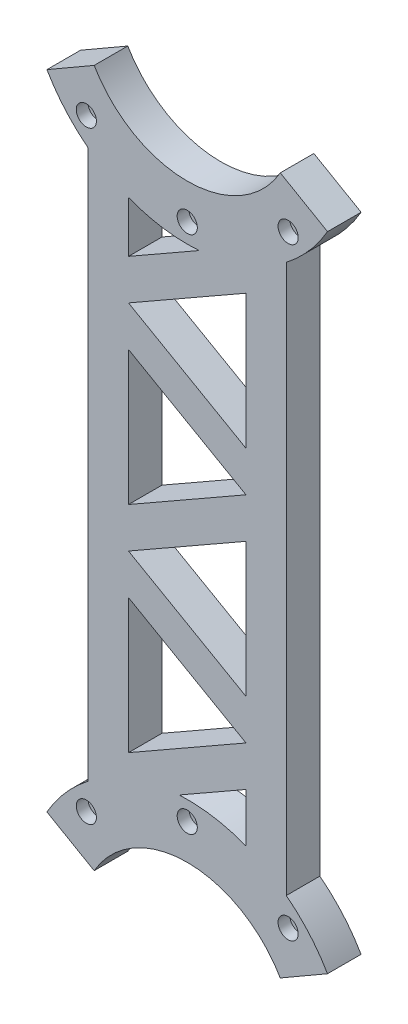
SolidWorks part; units mm, degrees
ref_plane "Front Plane" through (0, 0, 0) normal (0, 0, 1) x (1, 0, 0)
ref_plane "Top Plane" through (0, 0, 0) normal (0, 1, 0) x (1, 0, 0)
ref_plane "Right Plane" through (0, 0, 0) normal (1, 0, 0) x (0, 0, -1)
sketch "Sketch1" plane through (0, 0, 0) normal (0, 0, 1) x (1, 0, 0)
  circle A0 centre (0, 0) radius 48.25
extrude "Boss-Extrude1" add sketch "Sketch1" against normal blind 10 contours A0
sketch "Sketch2" plane through (0, 0, 0) normal (0, 0, 1) x (1, 0, 0)
  line L1 (-63.412, 28.4111) -> (-46.25, 28.4111)
  line L2 (-63.412, 28.4111) -> (-63.412, -28.4111)
  line L3 (-63.412, -28.4111) -> (-46.25, -28.4111)
  line L4 (-46.25, 28.4111) -> (-46.25, -28.4111)
  line L5 (46.25, 28.4111) -> (62.4025, 28.4111)
  line L6 (46.25, 28.4111) -> (46.25, -36.7758)
  line L7 (46.25, -36.7758) -> (62.4025, -36.7758)
  line L8 (62.4025, 28.4111) -> (62.4025, -36.7758)
  dimension "D1" = 92.5
  dimension "D2" = 46.25
extrude "Cut-Extrude1" cut sketch "Sketch2" against normal blind 8 contours L5 L8 L7 L6 | L1 L4 L3 L2
sketch "Sketch3" plane through (0, 0, 0) normal (0, 0, 1) x (1, 0, 0)
  circle A0 centre (0, 0) radius 32
extrude "Cut-Extrude2" cut sketch "Sketch3" against normal blind 10 contours A0
sketch "Sketch4" plane through (0, 0, 0) normal (0, 0, 1) x (1, 0, 0)
  circle A0 centre (-42.5, 0) radius 1.75
  circle A1 centre (0, -42.5) radius 1.75
  circle A2 centre (0, 42.5) radius 1.75
  circle A3 centre (42.5, 0) radius 1.75
  circle A4 centre (-30.052, -30.052) radius 1.75
  circle A5 centre (30.052, -30.052) radius 1.75
  circle A6 centre (30.052, 30.052) radius 1.75
  circle A7 centre (-30.052, 30.052) radius 1.75
  point P10 (0, 0)
  point P13 (0, 0)
  point P16 (0, 0)
  point P19 (0, 0)
  point P22 (0, 0)
  point P25 (0, 0)
  dimension "D1" = 42.5
  dimension "D3" = 2
  dimension "D2" = 42.5
  dimension "D4" = 2
  dimension "D5" = 2
  dimension "D6" = 2
  dimension "D7" = 2
  dimension "D8" = 2
extrude "Cut-Extrude3" cut sketch "Sketch4" against normal blind 10
sketch "Sketch9" plane through (0, 0, 0) normal (0, 0, 1) x (1, 0, 0)
  circle A0 centre (-42.5, 0) radius 3
  circle A1 centre (42.5, 0) radius 3
  circle A2 centre (30.052, 30.052) radius 3
  circle A3 centre (-30.052, 30.052) radius 3
  circle A4 centre (-30.052, -30.052) radius 3
  circle A5 centre (30.052, -30.052) radius 3
  circle A6 centre (0, -42.5) radius 3
  circle A7 centre (0, 42.5) radius 3
sketch "Sketch10" plane through (0, 0, 0) normal (0, 0, 1) x (1, 0, 0)
  line L0 (0, 0) -> (0, 210) construction
  line L1 (-29.5, 0) -> (-29.5, 210)
  line L2 (29.5, 0) -> (29.5, 210)
  line L3 (-17.5, 39.54) -> (-17.5, 51.54)
  line L4 (-17.5, 215.0793) -> (17.5, 215.0793)
  line L5 (-17.5, 215.0793) -> (-17.5, -10.6365)
  line L6 (-17.5, -10.6365) -> (17.5, -10.6365)
  line L7 (17.5, 215.0793) -> (17.5, -10.6365)
  line L8 (-17.5, 39.54) -> (17.5, 59.54)
  line L9 (-17.5, 51.54) -> (17.5, 71.54)
  line L10 (17.5, 59.54) -> (17.5, 71.54)
  line L11 (17.5, 71.54) -> (17.5, 83.54)
  line L12 (17.5, 71.54) -> (-17.5, 91.54)
  line L13 (17.5, 83.54) -> (-17.5, 103.54)
  line L14 (-17.5, 91.54) -> (-17.5, 103.54)
  line L15 (-17.5, 103.54) -> (-17.5, 115.54)
  line L16 (-17.5, 103.54) -> (17.5, 123.54)
  line L17 (-17.5, 115.54) -> (17.5, 135.54)
  line L18 (17.5, 123.54) -> (17.5, 135.54)
  line L19 (17.5, 135.54) -> (17.5, 147.54)
  line L20 (17.5, 135.54) -> (-17.5, 155.54)
  line L21 (17.5, 147.54) -> (-17.5, 167.54)
  line L22 (-17.5, 155.54) -> (-17.5, 167.54)
  line L23 (-17.5, 167.54) -> (-17.5, 179.54)
  line L24 (-17.5, 167.54) -> (17.5, 187.54)
  line L25 (-17.5, 179.54) -> (17.5, 199.54)
  line L26 (17.5, 187.54) -> (17.5, 199.54)
  arc A0 (-29.5, 0) -> (29.5, 0) centre (0, 0) ccw
  arc A1 (29.5, 210) -> (-29.5, 210) centre (0, 210) ccw
  point P3 (0, 105)
  dimension "D1" = 12
  dimension "D2" = 12
  dimension "D3" = 12
  dimension "D4" = 20
  dimension "D5" = 12
  dimension "D6" = 20
  dimension "D7" = 12
  dimension "D8" = 20
  dimension "D9" = 12
  dimension "D10" = 20
  dimension "D11" = 12
  dimension "D12" = 20
extrude "Cut-Extrude4" cut sketch "Sketch9" against normal blind 3.5
sketch "Sketch12" plane through (0, 0, 0) normal (0, 0, 1) x (1, 0, 0)
  circle A0 centre (0, 239.6942) radius 48.25
  dimension "D1" = 0
extrude "Boss-Extrude4" add sketch "Sketch12" against normal blind 10 separate body contours A0
sketch "Sketch13" plane through (0, 0, 0) normal (0, 0, 1) x (1, 0, 0)
  line L1 (-63.412, 436.9676) -> (-46.25, 436.9676)
  line L2 (-63.412, 436.9676) -> (-63.412, 196.7016)
  line L3 (-63.412, 196.7016) -> (-46.25, 196.7016)
  line L4 (-46.25, 436.9676) -> (-46.25, 196.7016)
  line L5 (46.25, 187.19) -> (62.4025, 187.19)
  line L6 (46.25, 187.19) -> (46.25, 413.3722)
  line L7 (46.25, 413.3722) -> (62.4025, 413.3722)
  line L8 (62.4025, 187.19) -> (62.4025, 413.3722)
  dimension "D1" = 92.5
extrude "Cut-Extrude5" cut sketch "Sketch13" against normal blind 5
sketch "Sketch14" plane through (0, 0, 0) normal (0, 0, 1) x (1, 0, 0)
  circle A0 centre (0, 239.6942) radius 30
extrude "Cut-Extrude6" cut sketch "Sketch14" against normal blind 10 contours A0
sketch "Sketch17" plane through (0, 0, 0) normal (0, 0, 1) x (1, 0, 0)
  line L0 (0, 0) -> (-69.3043, 39.9614)
  line L1 (-69.3043, 39.9614) -> (-69.2783, -65.3223)
  line L2 (-69.2783, -65.3223) -> (63.9709, -62.4072)
  line L3 (63.9709, -62.4072) -> (69.2598, 40.0386)
  line L4 (69.2598, 40.0386) -> (0, 0)
  dimension "D1" = 120
  dimension "D2" = 80
  dimension "D3" = 80
extrude "Cut-Extrude7" cut sketch "Sketch17" against normal blind 10
sketch "Sketch18" plane through (0, 0, 0) normal (0, 0, 1) x (1, 0, 0)
  line L0 (0, 239.6942) -> (-69.2843, 199.698)
  line L1 (-69.2843, 199.698) -> (-69.0664, 357.5112)
  line L2 (-69.0664, 357.5112) -> (54.7017, 362.3334)
  line L3 (54.7017, 362.3334) -> (69.2798, 199.6903)
  line L4 (69.2798, 199.6903) -> (0, 239.6942)
  point P0 (69.2798, 199.698)
  dimension "D1" = 120
  dimension "D2" = 80
  dimension "D3" = 80
extrude "Cut-Extrude8" cut sketch "Sketch18" against normal blind 10
sketch "Sketch19" plane through (0, 0, 0) normal (0, 0, 1) x (1, 0, 0)
  line L0 (0, 0) -> (0, 210) construction
  circle A0 centre (0, 197.1942) radius 1.75
  circle A1 centre (0, 239.6942) radius 30 construction
  circle A2 centre (-30.052, 209.6421) radius 1.75
  circle A3 centre (30.052, 209.6421) radius 1.75
  point P12 (0, 239.6942)
  point P15 (0, 239.6942)
  dimension "D1" = 42.5
  dimension "D2" = 2
  dimension "D3" = 2
extrude "Cut-Extrude9" cut sketch "Sketch19" against normal blind 10
extrude "Boss-Extrude5" add sketch "Sketch10" against normal blind 10
sketch "Sketch21" plane through (0, 0, 0) normal (0, 0, 1) x (1, 0, 0)
  circle A0 centre (0, 239.6942) radius 32
extrude "Cut-Extrude11" cut sketch "Sketch21" against normal blind 10
sketch "Sketch22" plane through (0, 0, 0) normal (0, 0, 1) x (1, 0, 0)
  circle A0 centre (-30.052, 209.6421) radius 1.75
  circle A1 centre (30.052, 209.6421) radius 1.75
extrude "Cut-Extrude12" cut sketch "Sketch22" against normal blind 10
sketch "Sketch23" plane through (0, 0, 0) normal (0, 0, 1) x (1, 0, 0)
  circle A0 centre (-30.052, 209.6421) radius 3
  circle A1 centre (0, 197.1942) radius 3
  circle A2 centre (30.052, 209.6421) radius 3
  circle A3 centre (0, 42.5) radius 3
extrude "Cut-Extrude13" cut sketch "Sketch23" against normal blind 3.5
